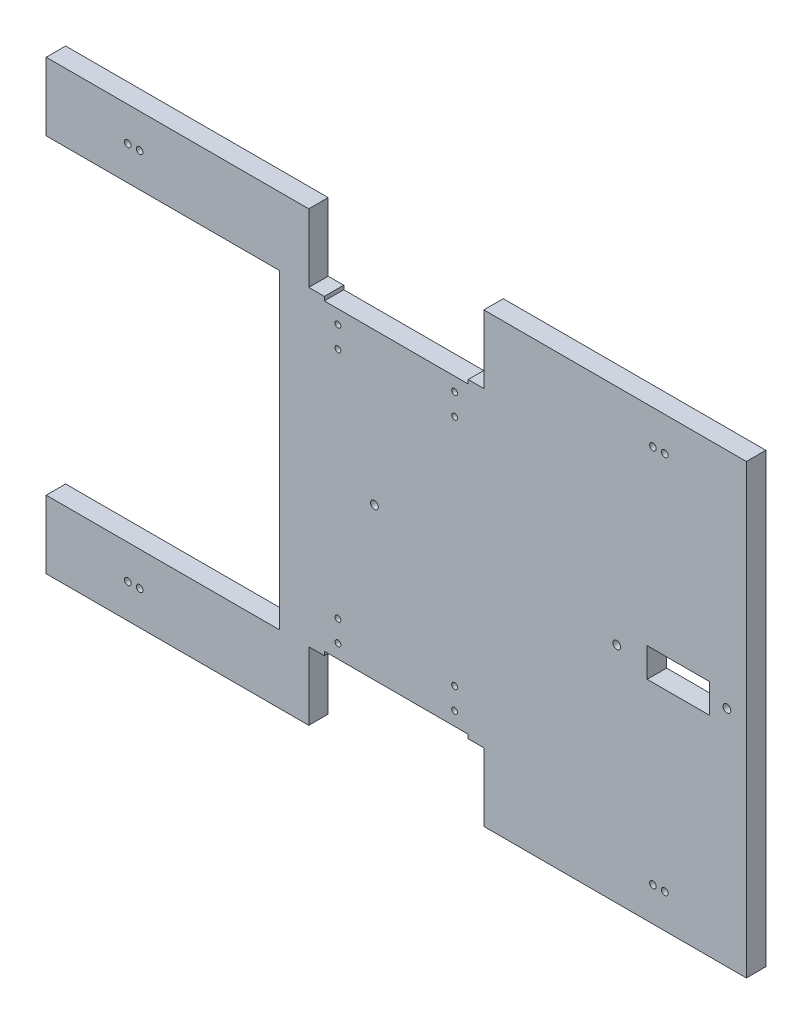
SolidWorks part; units mm, degrees
ref_plane "Front Plane" through (0, 0, 0) normal (0, 0, 1) x (1, 0, 0)
ref_plane "Top Plane" through (0, 0, 0) normal (0, 1, 0) x (1, 0, 0)
ref_plane "Right Plane" through (0, 0, 0) normal (1, 0, 0) x (0, 0, -1)
sketch "Sketch1" plane through (0, 0, 0) normal (0, 0, 1) x (1, 0, 0)
  line L0 (93.9503, 28.5381) -> (93.9503, -37.4187) construction
  line L1 (-86.0497, 116.3339) -> (48.9503, 116.3339)
  line L2 (-86.0497, 116.3339) -> (-86.0497, 81.3339)
  line L3 (-86.0497, -113.6661) -> (48.9503, -113.6661)
  line L4 (273.9503, 116.3339) -> (273.9503, -113.6661)
  line L5 (-41.0497, -98.231) -> (-41.0497, -94.1011) construction
  line L6 (130.9503, -76.6461) -> (130.9503, -78.6661)
  line L7 (33.9503, 1.3339) -> (273.9503, 1.3339) construction
  line L8 (-86.0497, -78.6661) -> (-86.0497, -113.6661)
  line L9 (-86.0497, 81.3339) -> (33.9503, 81.3339)
  line L10 (222.9503, 8.8339) -> (254.9503, 8.8339)
  line L11 (-86.0497, -78.6661) -> (33.9503, -78.6661)
  line L12 (33.9503, 81.3339) -> (33.9503, -78.6661)
  line L13 (222.9503, 8.8339) -> (222.9503, -6.1661)
  line L14 (130.9503, 81.3339) -> (138.9503, 81.3339)
  line L15 (93.9503, 82.3567) -> (93.9503, 76.2712) construction
  line L16 (48.9503, 116.3339) -> (48.9503, 81.3339)
  line L17 (48.9503, 81.3339) -> (56.9503, 81.3339)
  line L18 (138.9503, 116.3339) -> (138.9503, 81.3339)
  line L19 (138.9503, 116.3339) -> (273.9503, 116.3339)
  line L20 (138.9503, -113.6661) -> (138.9503, -78.6661)
  line L21 (130.9503, -78.6661) -> (138.9503, -78.6661)
  line L22 (56.9503, 81.3339) -> (56.9503, 79.3139)
  line L23 (56.9503, 79.3139) -> (130.9503, 79.3139)
  line L24 (130.9503, 81.3339) -> (130.9503, 79.3139)
  line L25 (48.9503, -113.6661) -> (48.9503, -78.6661)
  line L26 (48.9503, -78.6661) -> (56.9503, -78.6661)
  line L27 (56.9503, -78.6661) -> (56.9503, -76.6461)
  line L28 (56.9503, -76.6461) -> (130.9503, -76.6461)
  line L29 (138.9503, -113.6661) -> (273.9503, -113.6661)
  line L30 (39.4715, 1.3339) -> (28.4291, 1.3339) construction
  line L31 (222.9503, -6.1661) -> (254.9503, -6.1661)
  line L32 (254.9503, 8.8339) -> (254.9503, -6.1661)
  line L33 (222.9503, 8.8339) -> (254.9503, -6.1661) construction
  line L34 (222.9503, -6.1661) -> (254.9503, 8.8339) construction
  circle A0 centre (63.9503, 72.3139) radius 1.5
  circle A1 centre (63.9503, 61.3139) radius 1.5
  circle A2 centre (123.9503, 72.3139) radius 1.5
  circle A3 centre (123.9503, 61.3139) radius 1.5
  circle A4 centre (63.9503, -69.6461) radius 1.5
  circle A5 centre (63.9503, -58.6461) radius 1.5
  circle A6 centre (123.9503, -69.6461) radius 1.5
  circle A7 centre (123.9503, -58.6461) radius 1.5
  circle A8 centre (-44.0997, -96.1661) radius 1.7
  circle A9 centre (-37.9997, -96.1661) radius 1.7
  circle A10 centre (-44.0997, 98.8339) radius 1.7
  circle A11 centre (-37.9997, 98.8339) radius 1.7
  circle A12 centre (232.0003, -96.1661) radius 1.7
  circle A13 centre (225.9003, -96.1661) radius 1.7
  circle A14 centre (225.9003, 98.8339) radius 1.7
  circle A15 centre (232.0003, 98.8339) radius 1.7
  circle A16 centre (82.7187, 1.3339) radius 2
  circle A17 centre (207.295, 1.3339) radius 2
  circle A18 centre (263.9503, 1.3339) radius 2
  point P4 (93.9503, 1.3825)
  point P28 (93.9503, 79.3139)
  point P55 (33.9503, 1.3339)
  point P58 (-41.0497, -96.1661)
  point P80 (238.9503, 1.3339)
  dimension "D9" = 3
  dimension "D10" = 3
  dimension "D15" = 17.5
  dimension "D16" = 3.4
  dimension "D18" = 4
  dimension "D19" = 4
  dimension "D20" = 4
  dimension "D1" = 230
  dimension "D2" = 360
  dimension "D3" = 160
  dimension "D4" = 90
  dimension "D5" = 35
  dimension "D6" = 120
  dimension "D7" = 74
  dimension "D8" = 2.02
  dimension "D11" = 7
  dimension "D12" = 7
  dimension "D13" = 11
  dimension "D14" = 3.05
  dimension "D17" = 45
  dimension "D21" = 10
  dimension "D22" = 32
  dimension "D23" = 15
  dimension "D24" = 35
  dimension "D25" = 8
  dimension "D26" = 135
extrude "Boss-Extrude1" add sketch "Sketch1" along normal blind 10
